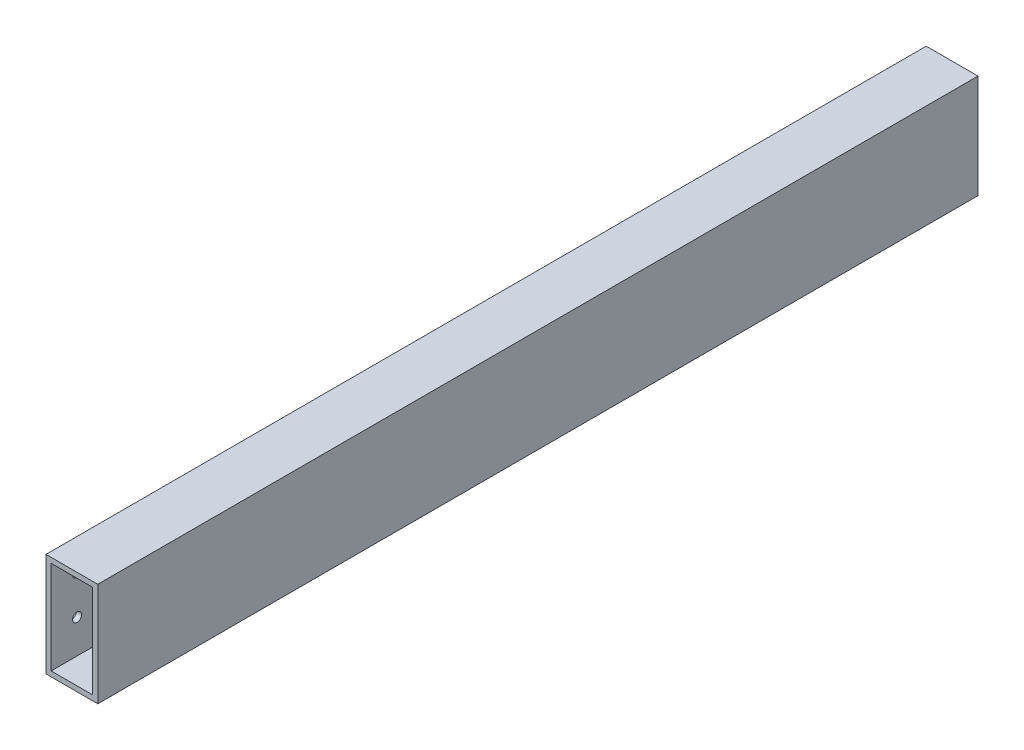
SolidWorks part; units mm, degrees
ref_plane "Plano frontal" through (0, 0, 0) normal (0, 0, 1) x (1, 0, 0)
ref_plane "Plano superior" through (0, 0, 0) normal (0, 1, 0) x (1, 0, 0)
ref_plane "Plano direito" through (0, 0, 0) normal (1, 0, 0) x (0, 0, -1)
sketch "Esboço1" plane through (0, 0, 0) normal (0, 0, 1) x (1, 0, 0)
  line L2 (0, 0) -> (20, 0)
  line L3 (0, 0) -> (0, 40)
  line L4 (0, 40) -> (20, 40)
  line L5 (20, 0) -> (20, 40)
  line L7 (2, 2) -> (18, 2)
  line L8 (2, 2) -> (2, 38)
  line L9 (2, 38) -> (18, 38)
  line L10 (18, 2) -> (18, 38)
  dimension "D1" = 40
  dimension "D2" = 20
  dimension "D3" = 2
  dimension "D4" = 2
  dimension "D5" = 2
  dimension "D6" = 2
extrude "Ressalto-extrusão1" add sketch "Esboço1" along normal blind 340
sketch "Esboço2" plane through (0, 0, 0) normal (-1, 0, 0) x (0, 0, 1)
  line L0 (0, 40) -> (0, 0) construction
  line L1 (340, 0) -> (0, 0) construction
  line L2 (170, 40) -> (170, 0) construction
  line L3 (340, 40) -> (0, 40) construction
  circle A0 centre (10, 30) radius 1.75
  circle A1 centre (10, 15) radius 1.75
  circle A2 centre (70, 15) radius 1.75
  circle A3 centre (55, 15) radius 1.75
  circle A4 centre (270, 15) radius 1.75
  circle A5 centre (285, 15) radius 1.75
  circle A6 centre (330, 15) radius 1.75
  circle A7 centre (330, 30) radius 1.75
  dimension "D1" = 3.5
  dimension "D2" = 3.5
  dimension "D7" = 3.5
  dimension "D8" = 3.5
  dimension "D3" = 10
  dimension "D4" = 15
  dimension "D5" = 15
  dimension "D6" = 10
  dimension "D9" = 70
  dimension "D10" = 15
extrude "Corte-extrusão1" cut sketch "Esboço2" against normal blind 2
